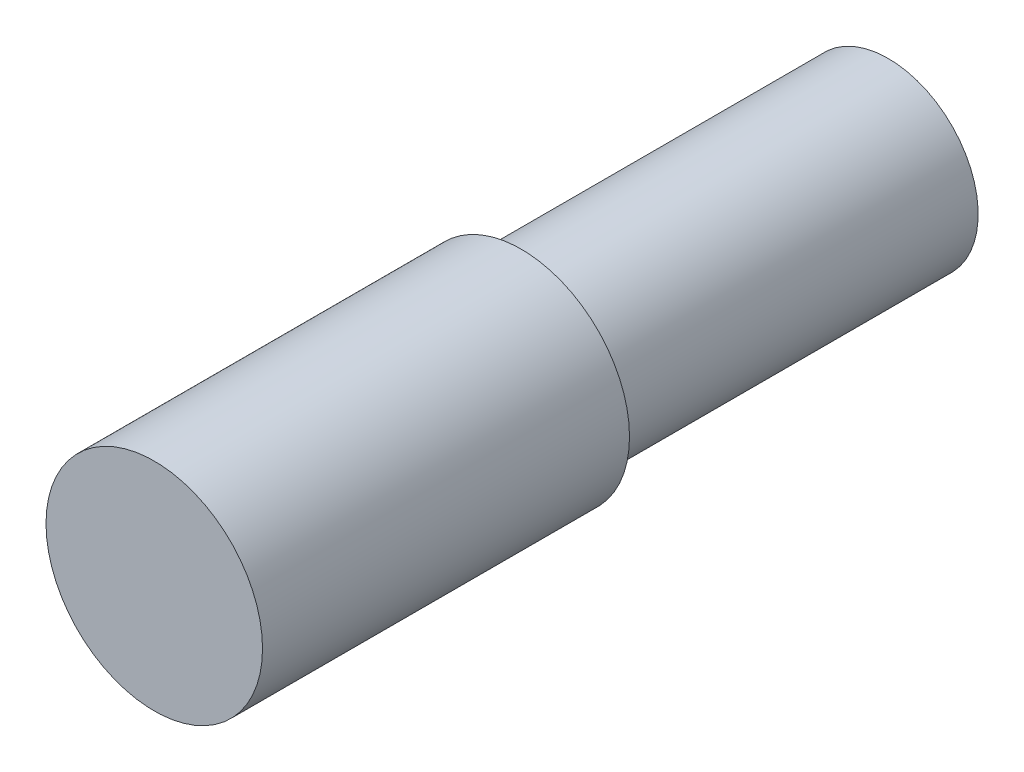
SolidWorks part; units mm, degrees
ref_plane "Ebene vorne" through (0, 0, 0) normal (0, 0, 1) x (1, 0, 0)
ref_plane "Ebene oben" through (0, 0, 0) normal (0, 1, 0) x (1, 0, 0)
ref_plane "Ebene rechts" through (0, 0, 0) normal (1, 0, 0) x (0, 0, -1)
sketch "Skizze1" plane through (0, 0, 0) normal (0, 0, 1) x (1, 0, 0)
  circle A0 centre (0, 0) radius 2.95
  dimension "D1" = 5.9
extrude "Aufsatz-Linear austragen1" add sketch "Skizze1" along normal blind 10
sketch "Skizze2" plane through (0, 0, 0) normal (0, 0, -1) x (-1, 0, 0)
  circle A0 centre (0, 0) radius 2.45
  dimension "D1" = 4.9
extrude "Aufsatz-Linear austragen2" add sketch "Skizze2" along normal blind 10
